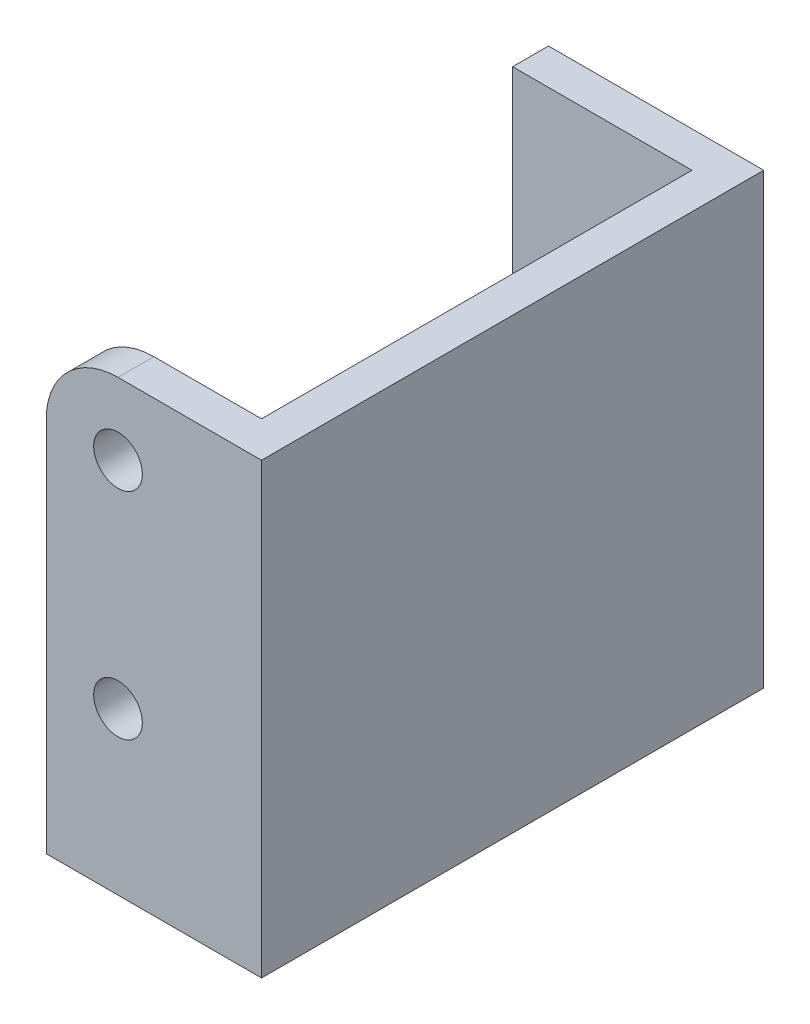
SolidWorks part; units mm, degrees
material "PET"
ref_plane "Front Plane" through (0, 0, 0) normal (0, 0, 1) x (1, 0, 0)
ref_plane "Top Plane" through (0, 0, 0) normal (0, 1, 0) x (1, 0, 0)
ref_plane "Right Plane" through (0, 0, 0) normal (1, 0, 0) x (0, 0, -1)
sketch "Sketch1" plane through (0, 0, 0) normal (0, 0, 1) x (1, 0, 0)
  line L1 (-9.525, 19.8438) -> (9.525, 19.8438)
  line L2 (-9.525, 19.8438) -> (-9.525, -19.8437)
  line L3 (-9.525, -19.8437) -> (9.525, -19.8437)
  line L4 (9.525, 19.8438) -> (9.525, -19.8437)
  line L5 (-9.525, 19.8438) -> (9.525, -19.8437) construction
  line L6 (-9.525, -19.8437) -> (9.525, 19.8438) construction
  point P0 (0, 0)
  dimension "D1" = 39.6875
  dimension "D2" = 19.05
extrude "Boss-Extrude1" add sketch "Sketch1" against normal blind 44.45
shell "Shell1" thickness 3.175
sketch "Sketch2" plane through (0, 0, 0) normal (0, 0, 1) x (1, 0, 0)
  line L0 (9.525, 19.8438) -> (-9.525, 19.8438) construction
  line L1 (-9.525, 19.8438) -> (-9.525, -19.8437) construction
  circle A0 centre (-3.175, -5.5562) radius 2.1526
  circle A1 centre (-3.175, 13.4938) radius 2.1526
  point P8 (0, 0)
  dimension "D1" = 4.3053
  dimension "D2" = 19.05
  dimension "D3" = 6.35
  dimension "D4" = 6.35
extrude "Cut-Extrude1" cut sketch "Sketch2" against normal up to next
fillet "Fillet2" radius 6.35 1 edges at (-9.525, 19.8438, -1.5875)
